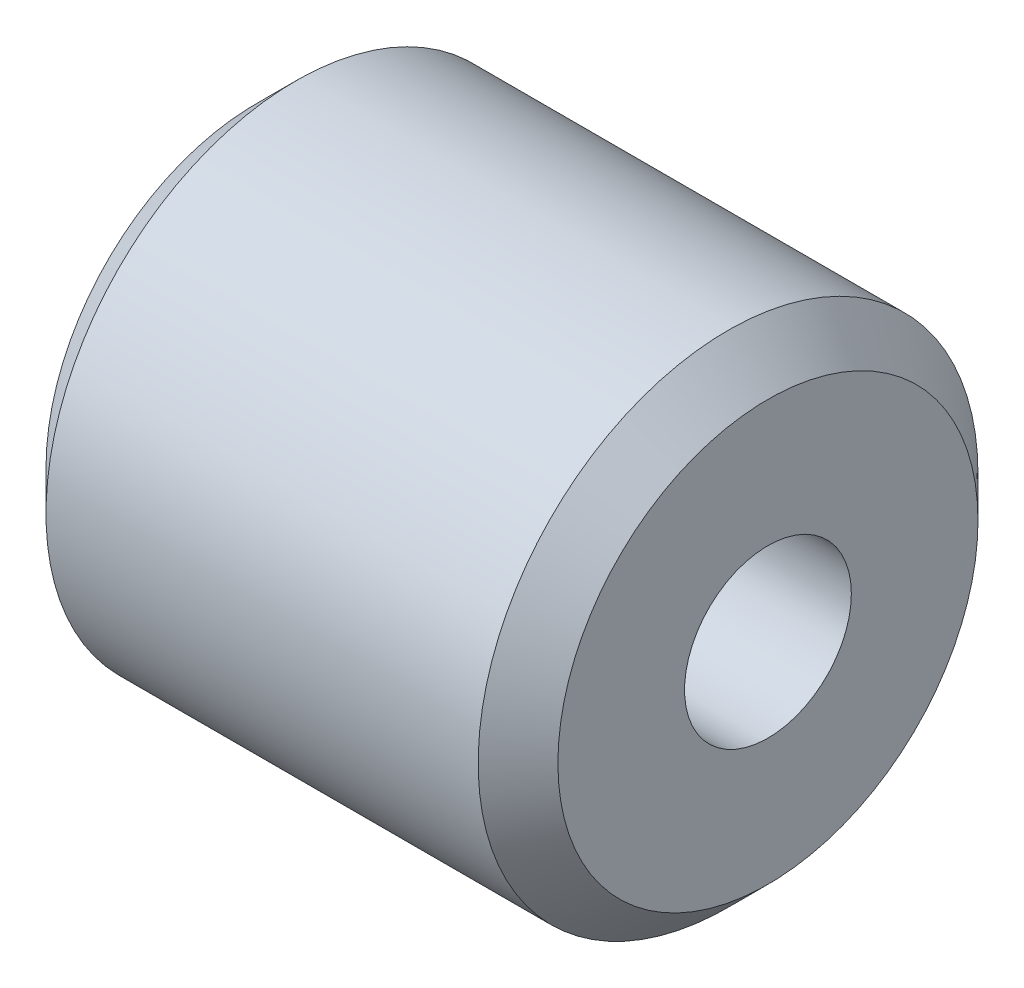
SolidWorks part; units mm, degrees
ref_plane "Front Plane" through (0, 0, 0) normal (0, 0, 1) x (1, 0, 0)
ref_plane "Top Plane" through (0, 0, 0) normal (0, 1, 0) x (1, 0, 0)
ref_plane "Right Plane" through (0, 0, 0) normal (1, 0, 0) x (0, 0, -1)
sketch "Sketch1" plane through (0, 0, 0) normal (1, 0, 0) x (0, 0, -1)
  circle A0 centre (0, 0) radius 4.765
  circle A1 centre (0, 0) radius 1.59
  dimension "D1" = 9.53
  dimension "D2" = 3.18
extrude "Boss-Extrude1" add sketch "Sketch1" along normal mid plane 9.76
chamfer "Chamfer1" distance 0.76 angle 45 2 edges at (-4.88, 0, -4.765) (4.88, 0, -4.765)
